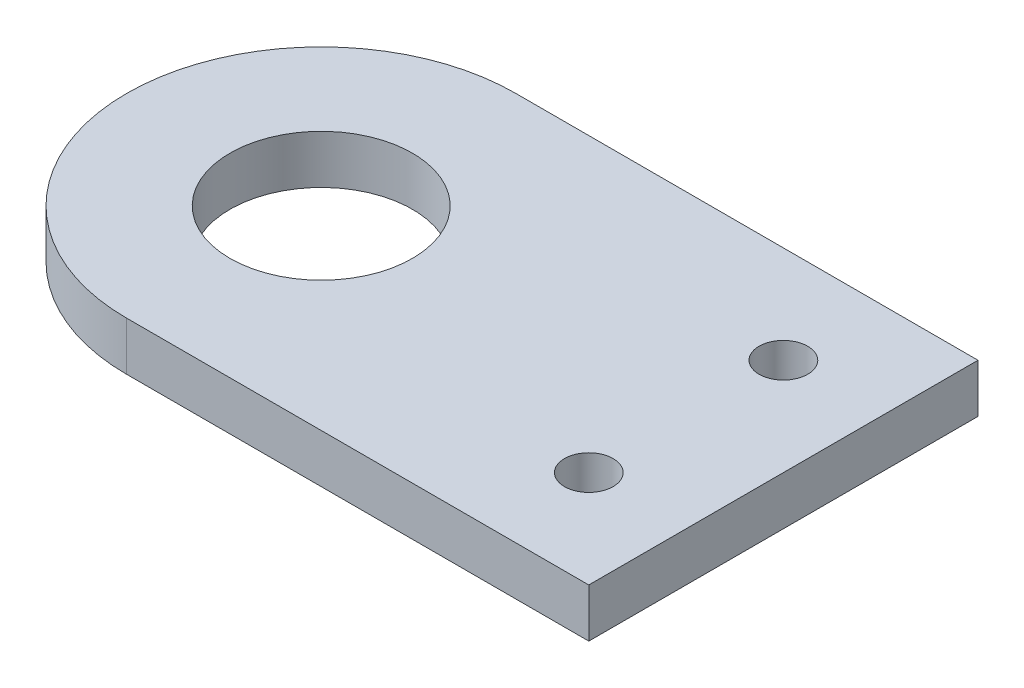
SolidWorks part; units mm, degrees
ref_plane "Front" through (0, 0, 0) normal (0, 0, 1) x (1, 0, 0)
ref_plane "Top" through (0, 0, 0) normal (0, 1, 0) x (1, 0, 0)
ref_plane "Right" through (0, 0, 0) normal (1, 0, 0) x (0, 0, -1)
sketch "Sketch1" plane through (0, 0, 0) normal (0, 1, 0) x (1, 0, 0)
  line L0 (0, 16) -> (38, 16)
  line L1 (38, 16) -> (38, -16)
  line L2 (38, -16) -> (0, -16)
  circle A0 centre (0, 0) radius 16
  circle A1 centre (0, 0) radius 7.5
  dimension "D1" = 38
extrude "Boss-Extrude1" add sketch "Sketch1" along normal blind 4 contours A0 A1 | A0 L2 L1 L0
sketch "Sketch2" plane through (0, 4, 0) normal (0, 1, 0) x (1, 0, 0)
  line L0 (38, 0) -> (30, 0)
  line L1 (38, 16) -> (38, -16) construction
  line L2 (30, 0) -> (30, 8)
  line L3 (30, 8) -> (30, -8)
  circle A0 centre (30, -8) radius 2
  circle A1 centre (30, 8) radius 2
  dimension "D1" = 8
  dimension "D2" = 8
  dimension "D3" = 30
extrude "Cut-Extrude1" cut sketch "Sketch2" against normal through all
sketch "Sketch3" plane through (0, 4, 0) normal (0, 1, 0) x (1, 0, 0)
  circle A0 centre (0, 0) radius 7.5
  circle A1 centre (0, 0) radius 16
extrude "Boss-Extrude2" [suppressed] add sketch "Sketch3" along normal blind 2
